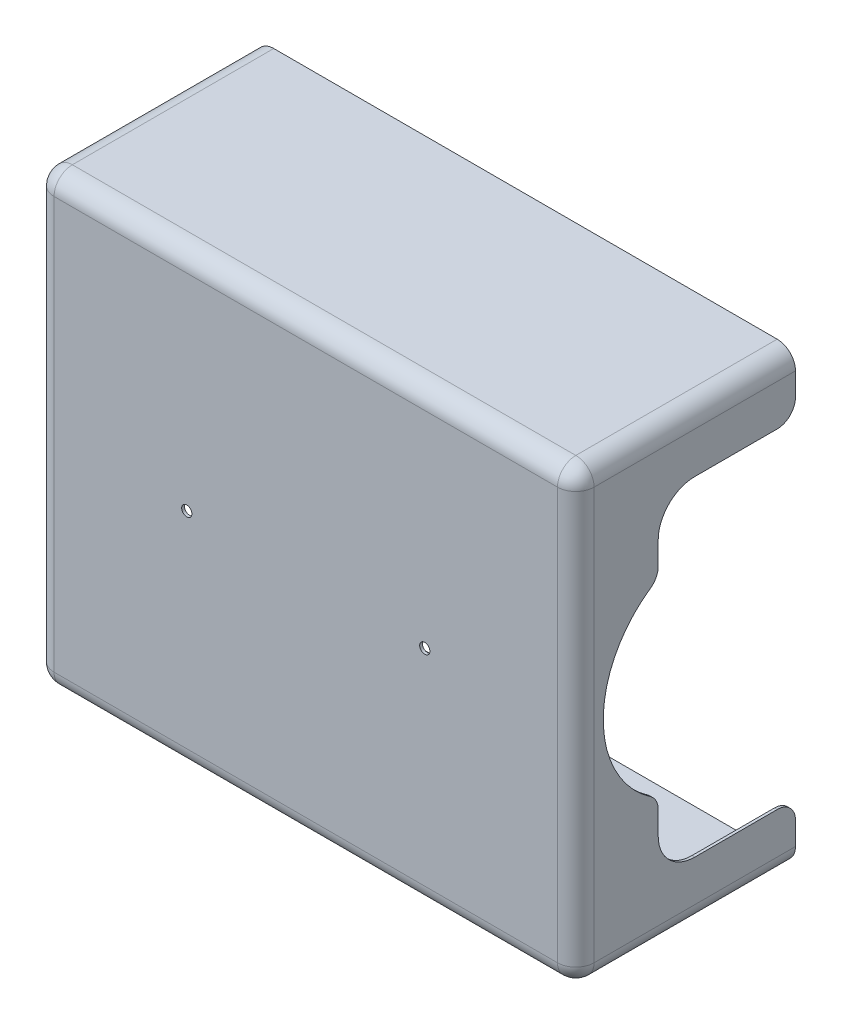
SolidWorks part; units mm, degrees
ref_plane "前视基准面" through (0, 0, 0) normal (0, 0, 1) x (1, 0, 0)
ref_plane "上视基准面" through (0, 0, 0) normal (0, 1, 0) x (1, 0, 0)
ref_plane "右视基准面" through (0, 0, 0) normal (1, 0, 0) x (0, 0, -1)
sketch "草图1" plane through (0, 0, 0) normal (0, 0, 1) x (1, 0, 0)
  line L1 (-147.5, 122.5) -> (147.5, 122.5)
  line L2 (-147.5, 122.5) -> (-147.5, -122.5)
  line L3 (-147.5, -122.5) -> (147.5, -122.5)
  line L4 (147.5, 122.5) -> (147.5, -122.5)
  line L5 (-147.5, 122.5) -> (147.5, -122.5) construction
  line L6 (-147.5, -122.5) -> (147.5, 122.5) construction
  point P0 (0, 0)
  dimension "D1" = 295
  dimension "D2" = 245
extrude "凸台-拉伸1" add sketch "草图1" along normal blind 120
fillet "圆角1" radius 10 8 edges at (-147.5, 122.5, 60) (147.5, 122.5, 60) (-147.5, -122.5, 60) (147.5, -122.5, 60) (0, -122.5, 120) (-147.5, 0, 120) (0, 122.5, 120) (147.5, 0, 120)
shell "抽壳1" thickness 1.5
sketch "草图2" plane through (-147.5, 0, 0) normal (-1, 0, 0) x (0, 0, 1)
  line L0 (0, 0) -> (45, 0) construction
  line L2 (-45, 60) -> (45, 60)
  line L3 (-45, 60) -> (-45, -60)
  line L4 (-45, -60) -> (45, -60)
  line L5 (45, 60) -> (45, -60)
  line L6 (-45, 60) -> (45, -60) construction
  line L7 (-45, -60) -> (45, 60) construction
  circle A0 centre (45, 0) radius 60
  line M5 (0, 112.5) -> (0, -112.5)
  dimension "D1" = 120
  dimension "D2" = 45
extrude "切除-拉伸1" cut sketch "草图2" against normal through all contours L5 A0 | L5 A0 M5 | A0 M5 | A0 L2 M5 | A0 L4 M5
sketch "草图3" plane through (-147.5, 0, 0) normal (-1, 0, 0) x (0, 0, 1)
  line L1 (-75, -30) -> (75, -30)
  line L2 (-75, -30) -> (-75, -90)
  line L3 (-75, -90) -> (75, -90)
  line L4 (75, -30) -> (75, -90)
  line L5 (-75, -30) -> (75, -90) construction
  line L6 (-75, -90) -> (75, -30) construction
  line L7 (-75, 90) -> (75, 90)
  line L8 (-75, 90) -> (-75, 30)
  line L9 (-75, 30) -> (75, 30)
  line L10 (75, 90) -> (75, 30)
  line L11 (-75, 90) -> (75, 30) construction
  line L12 (-75, 30) -> (75, 90) construction
  point P0 (0, -60)
  point P6 (0, 60)
  dimension "D1" = 60
  dimension "D2" = 150
extrude "切除-拉伸2" cut sketch "草图3" against normal through all
fillet "圆角2" radius 10 8 edges at (146.75, 90, 0) (146.75, -90, 0) (-146.75, -90, 0) (-146.75, 90, 0) (146.75, 51.9615, 75) (146.75, -51.9615, 75) (-146.75, -51.9615, 75) (-146.75, 51.9615, 75)
fillet "圆角3" radius 20 4 edges at (-146.75, -90, 75) (-146.75, 90, 75) (146.75, -90, 75) (146.75, 90, 75)
sketch "草图4" plane through (0, 0, 120) normal (0, 0, 1) x (1, 0, 0)
  circle A0 centre (-65, 0) radius 2.8
  circle A1 centre (65, 0) radius 2.8
extrude "切除-拉伸3" cut sketch "草图4" against normal blind 10
